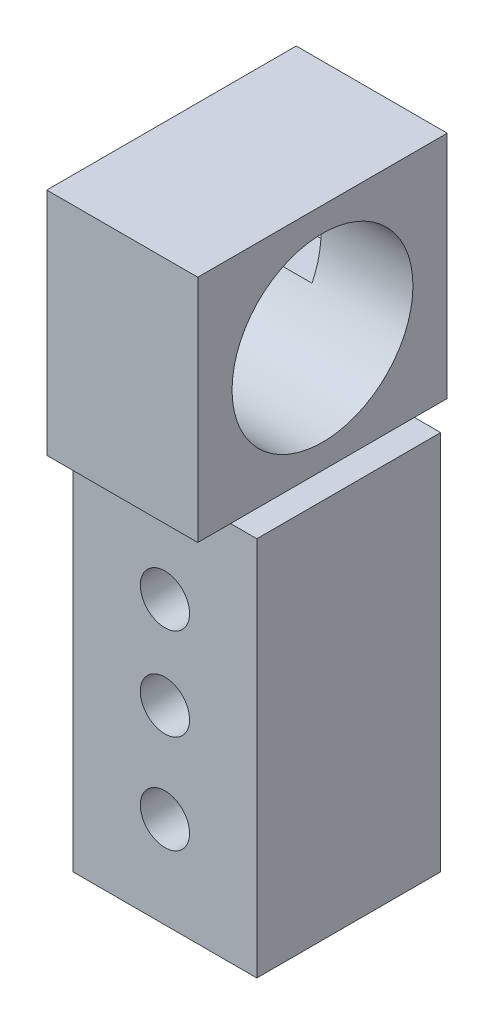
SolidWorks part; units mm, degrees
ref_plane "Front Plane" through (0, 0, 0) normal (0, 0, 1) x (1, 0, 0)
ref_plane "Top Plane" through (0, 0, 0) normal (0, 1, 0) x (1, 0, 0)
ref_plane "Right Plane" through (0, 0, 0) normal (1, 0, 0) x (0, 0, -1)
sketch "Sketch1" plane through (0, 0, 0) normal (0, 1, 0) x (1, 0, 0)
  line L1 (17.78, -17.78) -> (-17.78, -17.78)
  line L2 (17.78, -17.78) -> (17.78, 17.78)
  line L3 (17.78, 17.78) -> (-17.78, 17.78)
  line L4 (-17.78, -17.78) -> (-17.78, 17.78)
  line L5 (17.78, -17.78) -> (-17.78, 17.78) construction
  line L6 (17.78, 17.78) -> (-17.78, -17.78) construction
  point P0 (0, 0)
  dimension "D1" = 35.56
  dimension "D2" = 35.56
extrude "Boss-Extrude1" add sketch "Sketch1" against normal blind 73.5965
sketch "Sketch2" plane through (0, 0, 17.78) normal (0, 0, 1) x (1, 0, 0)
  line L0 (-17.78, 0) -> (17.78, 0) construction
  line L4 (17.78, -73.5965) -> (17.78, 0) construction
  circle A1 centre (0, -19.05) radius 4.7625
  circle A2 centre (0, -36.83) radius 4.7625
  circle A3 centre (0, -55.88) radius 4.7625
  dimension "D4" = 19.05
  dimension "D5" = 9.525
  dimension "D6" = 9.525
  dimension "D7" = 9.525
  dimension "D2" = 17.78
  dimension "D3" = 19.05
  dimension "D8" = 55.88
  dimension "D10" = 17.78
  dimension "D12" = 17.78
extrude "Cut-Extrude1" cut sketch "Sketch2" against normal through all
sketch "Sketch3" plane through (0, 0, 0) normal (0, 1, 0) x (1, 0, 0)
  line L0 (-17.78, -17.78) -> (17.78, -17.78) construction
  line L1 (12.7, 17.78) -> (-12.7, 17.78)
  line L2 (12.7, 17.78) -> (12.7, -17.78)
  line L3 (12.7, -17.78) -> (-12.7, -17.78)
  line L4 (-12.7, 17.78) -> (-12.7, -17.78)
  line L5 (12.7, 17.78) -> (-12.7, -17.78) construction
  line L6 (12.7, -17.78) -> (-12.7, 17.78) construction
  line L7 (-17.78, 17.78) -> (-17.78, -17.78) construction
  line L8 (17.78, -17.78) -> (17.78, 17.78) construction
  point P0 (0, 0)
  dimension "D1" = 30.48
  dimension "D2" = 30.48
  dimension "D3" = 35.56
extrude "Boss-Extrude2" add sketch "Sketch3" along normal blind 44.45
sketch "Sketch5" plane through (0, 0, 17.78) normal (0, 0, 1) x (1, 0, 0)
  line L1 (-12.7, 44.45) -> (12.7, 44.45)
  line L2 (-12.7, 44.45) -> (-12.7, 0)
  line L3 (-12.7, 0) -> (12.7, 0)
  line L4 (12.7, 44.45) -> (12.7, 0)
extrude "Boss-Extrude3" add sketch "Sketch5" along normal blind 6.35
sketch "Sketch6" plane through (0, 0, -17.78) normal (0, 0, -1) x (-1, 0, 0)
  line L1 (-12.7, 44.45) -> (12.7, 44.45)
  line L2 (-12.7, 44.45) -> (-12.7, 0)
  line L3 (-12.7, 0) -> (12.7, 0)
  line L4 (12.7, 44.45) -> (12.7, 0)
extrude "Boss-Extrude4" add sketch "Sketch6" along normal blind 6.35
sketch "Sketch4" plane through (12.7, 0, 0) normal (1, 0, 0) x (0, 0, -1)
  line L0 (-24.13, 44.45) -> (24.13, 44.45) construction
  line L3 (-17.78, 44.45) -> (-17.78, 0) construction
  circle A0 centre (0, 22.225) radius 17.5
  dimension "D1" = 22.225
  dimension "D2" = 35
  dimension "D3" = 17.78
extrude "Cut-Extrude2" cut sketch "Sketch4" against normal through all
sketch "Sketch8" plane through (-12.7, 0, 0) normal (-1, 0, 0) x (0, 0, 1)
  line L0 (-24.13, 0) -> (-24.13, 44.45) construction
  line L1 (-24.13, 29.845) -> (-12.945, 29.845)
  line L2 (-24.13, 29.845) -> (-24.13, 14.605)
  line L3 (-24.13, 14.605) -> (-12.945, 14.605)
  line L4 (-12.945, 29.845) -> (-12.945, 14.605)
  point P6 (-24.13, 22.225)
  point P7 (-24.13, 22.225)
  dimension "D1" = 15.24
  dimension "D2" = 11.185
extrude "Cut-Extrude3" cut sketch "Sketch8" against normal blind 7.62
sketch "Sketch9" plane through (-12.7, 0, 0) normal (-1, 0, 0) x (0, 0, 1)
  line L1 (-24.13, 0) -> (24.13, 0)
  line L2 (-24.13, 0) -> (-24.13, 44.45)
  line L3 (-24.13, 44.45) -> (24.13, 44.45)
  line L4 (24.13, 0) -> (24.13, 44.45)
  line L5 (-24.13, 0) -> (24.13, 44.45) construction
  line L6 (-24.13, 44.45) -> (24.13, 0) construction
  point P0 (0, 22.225)
extrude "Boss-Extrude6" add sketch "Sketch9" along normal blind 3.81
sketch "Sketch12" plane through (-12.7, 0, 0) normal (1, 0, 0) x (0, 0, -1)
  line L1 (24.13, 14.605) -> (15.7539, 14.605)
  line L2 (24.13, 14.605) -> (24.13, 29.845)
  line L3 (24.13, 29.845) -> (15.7539, 29.845)
  line L4 (15.7539, 14.605) -> (15.7539, 29.845)
extrude "Cut-Extrude5" cut sketch "Sketch12" against normal up to surface (3.81 mm away) up to face at (-16.51, 14.8167, 0)
sketch "Sketch13" plane through (-16.51, 0, 0) normal (-1, 0, 0) x (0, 0, 1)
  line L0 (24.13, 44.45) -> (-24.13, 44.45) construction
  line L1 (24.13, 0) -> (24.13, 44.45) construction
  circle A0 centre (0, 21.9023) radius 5.588
  dimension "D1" = 11.176
  dimension "D3" = 24.13
  dimension "D2" = 22.5477
extrude "Cut-Extrude6" cut sketch "Sketch13" against normal up to surface (3.81 mm away) up to face at (-12.7, 22.225, 0.873)
sketch "Sketch14" plane through (-16.51, 0, 0) normal (-1, 0, 0) x (0, 0, 1)
  line L0 (24.13, 44.45) -> (-24.13, 44.45) construction
  line L1 (-24.13, 44.45) -> (-24.13, 29.845) construction
  line L2 (-24.13, 14.605) -> (-24.13, 0) construction
  line L3 (-24.13, 0) -> (-17.78, 0) construction
  line L4 (24.13, 0) -> (24.13, 44.45) construction
  line L5 (17.78, 0) -> (24.13, 0) construction
  line L6 (-24.13, 44.45) -> (24.13, 44.45) construction
  circle A0 centre (-6.604, 28.956) radius 1.5
  circle A1 centre (-8.89, 13.462) radius 1.5
  circle A2 centre (8.89, 30.988) radius 1.5
  circle A3 centre (6.604, 15.494) radius 1.5
  dimension "D3" = 3
  dimension "D4" = 3
  dimension "D9" = 3
  dimension "D10" = 3
  dimension "D2" = 17.526
  dimension "D5" = 15.24
  dimension "D6" = 13.462
  dimension "D7" = 15.24
  dimension "D8" = 13.462
  dimension "D11" = 17.526
  dimension "D12" = 15.494
  dimension "D13" = 0
  dimension "D14" = 15.494
extrude "Cut-Extrude7" cut sketch "Sketch14" against normal up to surface (3.81 mm away) up to face at (-12.7, 21.9023, -5.588)
